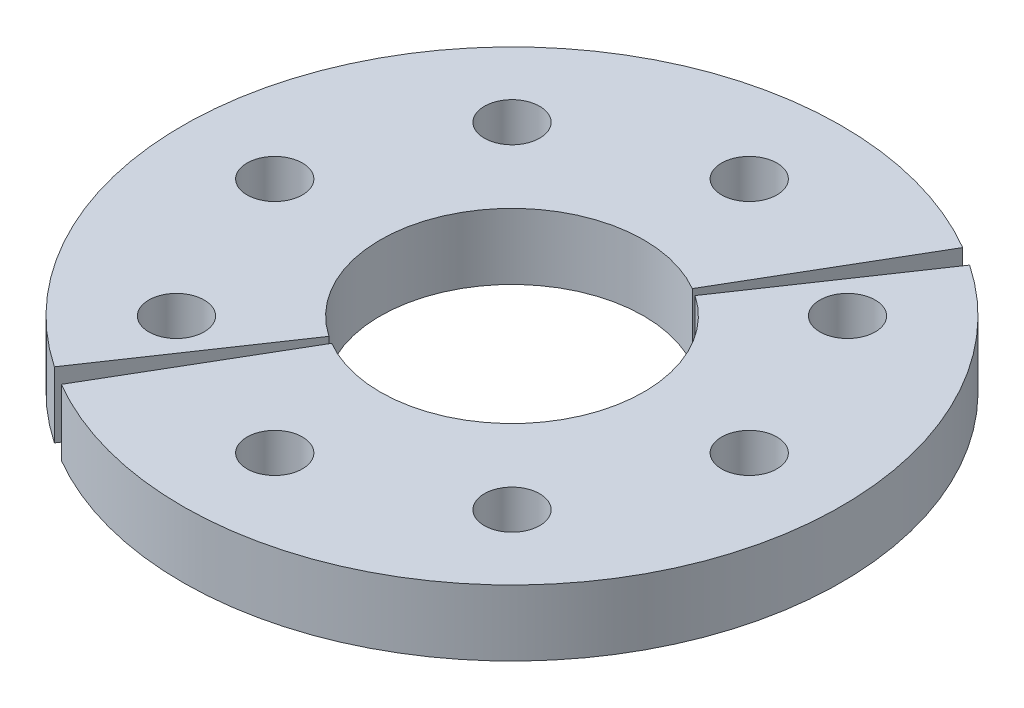
SolidWorks part; units mm, degrees
ref_plane "Спереди" through (0, 0, 0) normal (0, 0, 1) x (1, 0, 0)
ref_plane "Сверху" through (0, 0, 0) normal (0, 1, 0) x (1, 0, 0)
ref_plane "Справа" through (0, 0, 0) normal (1, 0, 0) x (0, 0, -1)
sketch "Эскиз1" plane through (0, 0, 0) normal (0, 1, 0) x (1, 0, 0)
  line L1 (-5.6063, -8.2806) -> (-14.0159, -20.7016)
  line L3 (-5.0408, -8.6366) -> (-12.602, -21.5914)
  line L4 (5.0408, 8.6366) -> (12.602, 21.5914)
  line L5 (5.6063, 8.2806) -> (14.0159, 20.7016)
  circle A0 centre (0, 0) radius 10
  circle A1 centre (0, 0) radius 25
  circle A3 centre (-18, 0) radius 2.1
  circle A4 centre (-12.7279, 12.7279) radius 2.1
  circle A5 centre (0, 18) radius 2.1
  circle A6 centre (12.7279, 12.7279) radius 2.1
  circle A7 centre (18, 0) radius 2.1
  circle A8 centre (12.7279, -12.7279) radius 2.1
  circle A9 centre (0, -18) radius 2.1
  circle A10 centre (-12.7279, -12.7279) radius 2.1
extrude "Бобышка-Вытянуть2" add sketch "Эскиз1" along normal blind 5 contours L4 A1 L1 A0 A10 A5 A4 A3 | L3 A1 L5 A0 A9 A8 A7 A6
